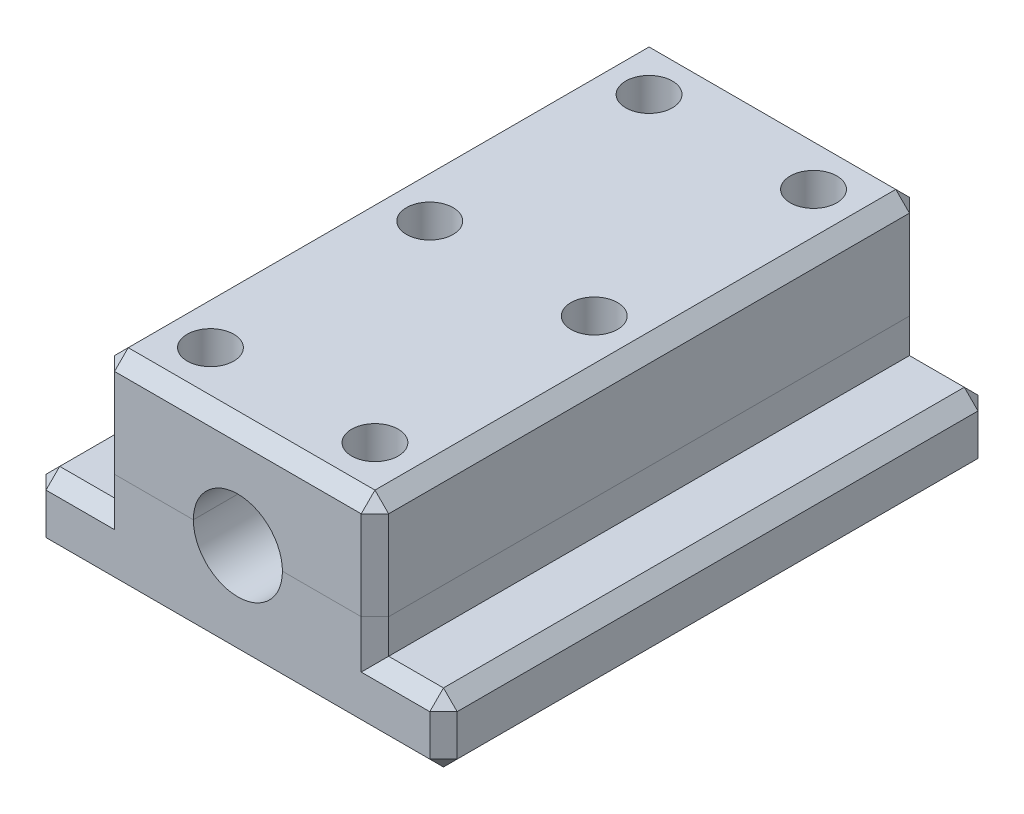
SolidWorks part; units mm, degrees
material "ABS"
ref_plane "Front Plane" through (0, 0, 0) normal (0, 0, 1) x (1, 0, 0)
ref_plane "Top Plane" through (0, 0, 0) normal (0, 1, 0) x (1, 0, 0)
ref_plane "Right Plane" through (0, 0, 0) normal (1, 0, 0) x (0, 0, -1)
sketch "Sketch1" plane through (0, 0, 0) normal (0, 0, 1) x (1, 0, 0)
  line L1 (-10, -7.5) -> (10, -7.5)
  line L2 (-10, -7.5) -> (-10, 7.5)
  line L3 (-10, 7.5) -> (10, 7.5)
  line L4 (10, -7.5) -> (10, 7.5)
  line L5 (-10, -7.5) -> (10, 7.5) construction
  line L6 (-10, 7.5) -> (10, -7.5) construction
  circle A0 centre (0, 0) radius 3.25
  point P0 (0, 0)
  dimension "D1" = 6.5
  dimension "D2" = 20
  dimension "D3" = 15
extrude "Boss-Extrude1" add sketch "Sketch1" along normal blind 40
hole_wizard "M3 Clearance Hole1" positions "Sketch4" profile "Sketch3" hole size "M3" standard "ISO" end condition through all
sketch "Sketch4" plane through (0, 7.5, 0) normal (0, 1, 0) x (1, 0, 0)
  line L0 (-10, -40) -> (-10, 0) construction
  line L1 (10, -40) -> (-10, -40) construction
  point P0 (-6, -36)
  dimension "D1" = 4
  dimension "D2" = 4
sketch "Sketch3" plane through (-6, 7.5, 36) normal (1, 0, 0) x (0, 0, 1)
  line L0 (0, 0) -> (0, 15)
  line L1 (0, 15) -> (1.7, 15)
  line L2 (1.7, 15) -> (1.7, 0)
  line L5 (1.7, 0) -> (0, 0)
  line L11 (0, -6.35) -> (0, 107.95) construction
  dimension "Thru Hole Dia." = 3.4
  dimension "Thru Hole Depth" = 15
pattern_linear "LPattern1" count 3 spacing 16 along (0, 0, -1) count 2 spacing 12 along (1, 0, 0) of "M3 Clearance Hole1"
sketch "Sketch5" plane through (0, 0, 40) normal (0, 0, 1) x (1, 0, 0)
  line L1 (10, -7.5) -> (15, -7.5)
  line L2 (10, -7.5) -> (10, -2.5)
  line L3 (10, -2.5) -> (15, -2.5)
  line L4 (15, -7.5) -> (15, -2.5)
  dimension "D1" = 5
  dimension "D2" = 5
extrude "Boss-Extrude3" add sketch "Sketch5" against normal up to surface (40 mm away) up to plane "Front Plane"
mirror "Mirror2" about plane through (0, 0, 0) normal (1, 0, 0) of "Boss-Extrude3"
chamfer "Chamfer1" distance 1 angle 45 22 edges at (-10, 2.5, 0) (-10, 2.5, 40) (10, 2.5, 0) (10, 2.5, 40) (15, -5, 0) (15, -5, 40) (12.5, -2.5, 0) (12.5, -2.5, 40) (0, -7.5, 0) (0, -7.5, 40) (-12.5, -2.5, 0) (-15, -5, 0) (-15, -7.5, 20) (-15, -2.5, 20) (-12.5, -2.5, 40) (-15, -5, 40) (15, -7.5, 20) (15, -2.5, 20) (0, 7.5, 0) (0, 7.5, 40) (-10, 7.5, 20) (10, 7.5, 20)
split "Split1" trim tools "Top Plane" bodies to split 109 resulting bodies 104 105
